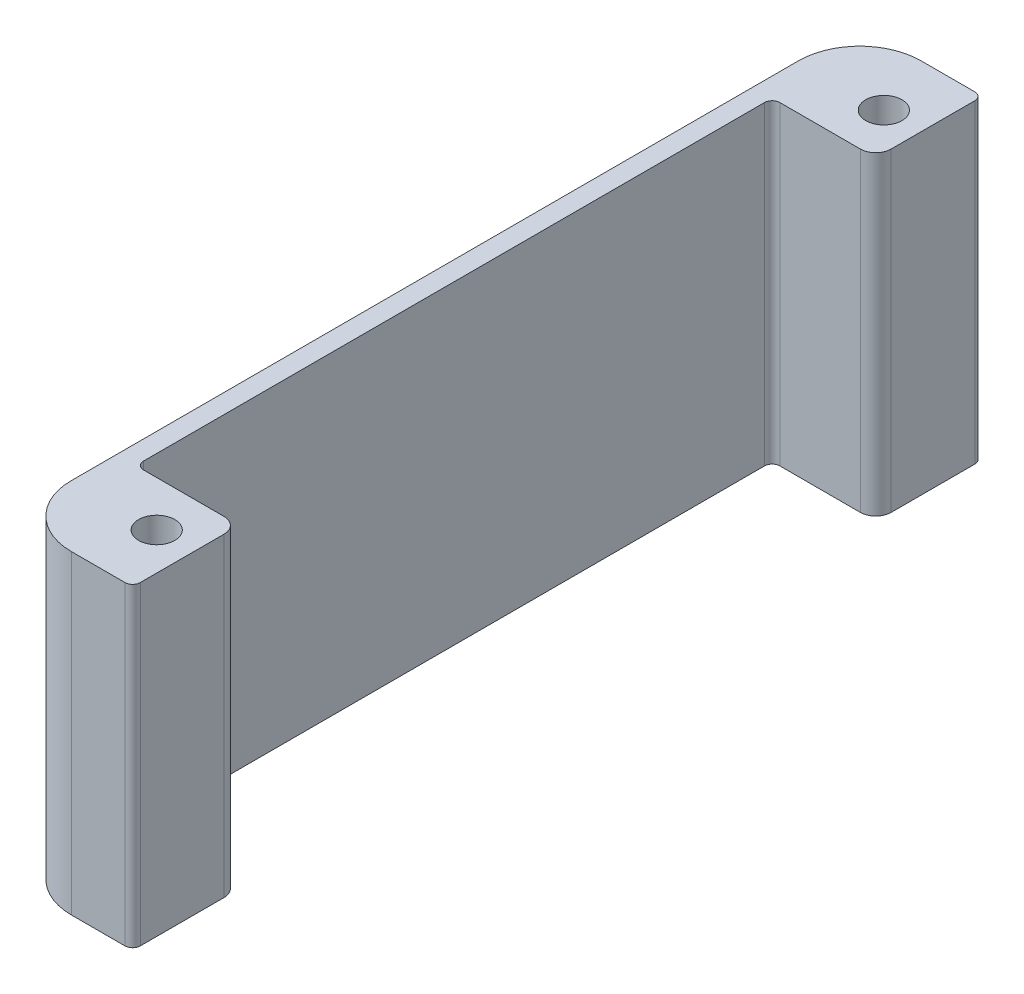
SolidWorks part; units mm, degrees
material "ABS"
ref_plane "X-Y Datum" through (0, 0, 0) normal (0, 0, 1) x (1, 0, 0)
ref_plane "X-Z Datum" through (0, 0, 0) normal (0, 1, 0) x (1, 0, 0)
ref_plane "Y-Z Datum" through (0, 0, 0) normal (1, 0, 0) x (0, 0, -1)
sketch "Sketch1" plane through (0, 0, 0) normal (0, 1, 0) x (1, 0, 0)
  line L0 (10.16, 127.3556) -> (10.16, 130.5306) construction
  line L1 (0, 0) -> (3.175, 0)
  line L2 (0, 0) -> (0, 120.3706)
  line L4 (3.175, 0) -> (3.175, 120.3706)
  line L5 (0, 60.1853) -> (14.4357, 60.1853) construction
  line L6 (10.16, -6.985) -> (10.16, -10.16) construction
  line L7 (10.16, 130.5306) -> (20.32, 130.5306)
  line L8 (20.32, 130.5306) -> (20.32, 127.3556)
  line L9 (20.32, 127.3556) -> (10.16, 127.3556)
  line L10 (10.16, -6.985) -> (20.32, -6.985)
  line L11 (20.32, -6.985) -> (20.32, -10.16)
  line L12 (20.32, -10.16) -> (10.16, -10.16)
  arc A0 (10.16, 130.5306) -> (0, 120.3706) centre (10.16, 120.3706) ccw
  arc A1 (10.16, 127.3556) -> (3.175, 120.3706) centre (10.16, 120.3706) ccw
  circle A2 centre (10.16, 120.3706) radius 10.16 construction
  circle A3 centre (10.16, 120.3706) radius 6.985 construction
  arc A4 (10.16, -6.985) -> (3.175, 0) centre (10.16, 0) cw
  arc A5 (10.16, -10.16) -> (0, 0) centre (10.16, 0) cw
  dimension "D1" = 3.175
extrude "Boss-Extrude1" add sketch "Sketch1" along normal blind 52.1 contours A1 L0 A0 L2 L1 L4 | A5 L6 A4 L1
sketch "Sketch2" plane through (0, 52.1, 0) normal (0, 1, 0) x (1, 0, 0)
  line L1 (3.175, 120.3706) -> (14.1478, 120.3706) construction
  line L3 (10.16, 112.857) -> (3.175, 112.857)
  line L4 (3.175, 0) -> (3.175, 120.3706) construction
  line L6 (20.32, 127.3556) -> (20.32, 112.857)
  line L7 (20.32, 127.3556) -> (10.16, 127.3556) construction
  line L8 (20.32, 112.857) -> (10.16, 112.857)
  circle A0 centre (14.1478, 120.3706) radius 3
  arc M6 (3.175, 120.3706) -> (10.16, 127.3556) centre (10.16, 120.3706) cw
  line M7 (10.16, 127.3556) -> (20.32, 127.3556)
  line M17 (3.175, 0) -> (3.175, 120.3706)
extrude "Boss-Extrude2" add sketch "Sketch2" along direction (0, 1, 0) on the side against the normal up to surface (52.1 mm away) contours L8 L6 L3 A0 M7 M6 M17
fillet "Fillet1" radius 2.54 1 edges at (20.32, 26.05, -112.857)
fillet "Fillet2" radius 1.27 1 edges at (3.175, 26.05, -112.857)
ref_plane "Plane1" through (0, 0, -60.1853) normal (0, 0, -1) x (-1, 0, 0)
mirror "Mirror1" about plane through (0, 0, -60.1853) normal (0, 0, -1) of "Fillet2", "Boss-Extrude2"
fillet "Fillet3" radius 1.27 2 edges at (20.32, 26.05, -130.5306) (20.32, 26.05, 10.16)
fillet "Fillet4" radius 2.54 1 edges at (20.32, 26.05, -7.5136)
